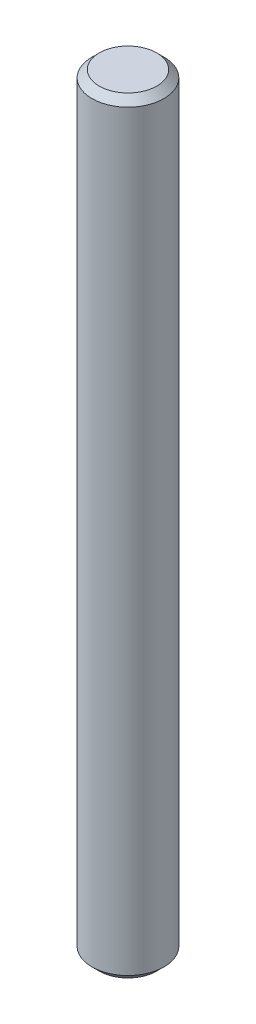
SolidWorks part; units mm, degrees
ref_plane "Front Plane" through (0, 0, 0) normal (0, 0, 1) x (1, 0, 0)
ref_plane "Top Plane" through (0, 0, 0) normal (0, 1, 0) x (1, 0, 0)
ref_plane "Right Plane" through (0, 0, 0) normal (1, 0, 0) x (0, 0, -1)
sketch "Sketch1" plane through (0, 0, 0) normal (0, 1, 0) x (1, 0, 0)
  circle A0 centre (0, 0) radius 0.5
  dimension "D1" = 1
extrude "Boss-Extrude1" add sketch "Sketch1" along normal blind 10 and the other way blind 0.65
chamfer "Chamfer1" distance 0.1 angle 45 2 edges at (0, -0.65, 0.5) (0, 10, 0.5)
